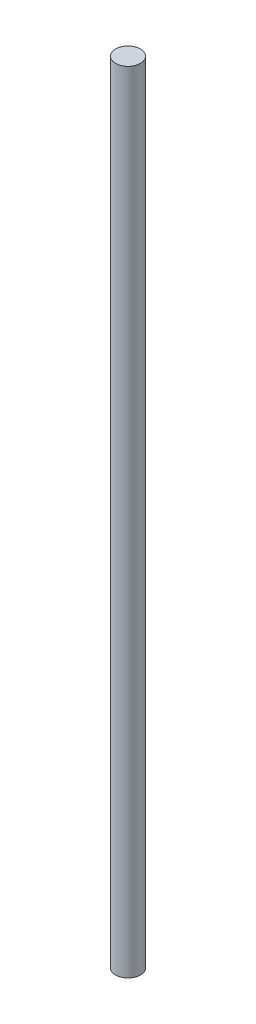
SolidWorks part; units mm, degrees
ref_plane "Front Plane" through (0, 0, 0) normal (0, 0, 1) x (1, 0, 0)
ref_plane "Top Plane" through (0, 0, 0) normal (0, 1, 0) x (1, 0, 0)
ref_plane "Right Plane" through (0, 0, 0) normal (1, 0, 0) x (0, 0, -1)
other "Configuration Table"
sketch "Sketch1" plane through (0, 0, 0) normal (0, 1, 0) x (1, 0, 0)
  circle A0 centre (150, 300) radius 6
extrude "OVEN_kesme_kilavuz_mili_D12_1" add sketch "Sketch1" along normal blind 380 from offset 400 separate body
